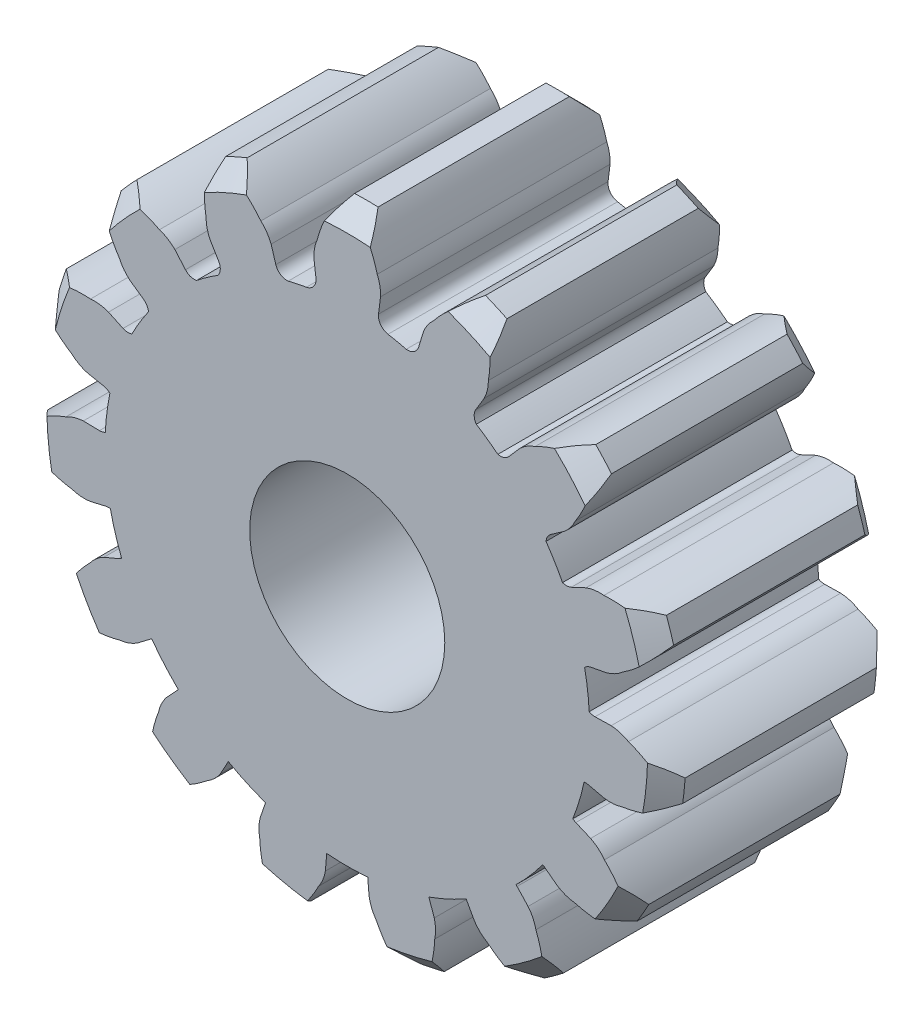
SolidWorks part; units mm, degrees
ref_plane "Front Plane" through (0, 0, 0) normal (0, 0, 1) x (1, 0, 0)
ref_plane "Top Plane" through (0, 0, 0) normal (0, 1, 0) x (1, 0, 0)
ref_plane "Right Plane" through (0, 0, 0) normal (1, 0, 0) x (0, 0, -1)
sketch "Sketch1" plane through (0, 0, 0) normal (0, 0, 1) x (1, 0, 0)
  circle A0 centre (0, 0) radius 6.333
  dimension "Di" = 12.666
extrude "Boss-Extrude1" add sketch "Sketch1" along normal blind 6
sketch "Sketch2" plane through (0, 0, 6) normal (0, 0, 1) x (1, 0, 0)
  line L0 (0, 0) -> (0, 64.154) construction
  line L2 (0.8182, 6.5755) -> (0.8702, 6.9938)
  line L3 (-0.8182, 6.5755) -> (-0.8702, 6.9938)
  line L4 (0.8182, 6.5755) -> (0, 0) construction
  arc A1 (0.0333, 6.7153) -> (0.0333, 6.7153) centre (0, 7.5) cw construction
  arc A8 (-0.3068, 8.4945) -> (0.3068, 8.4945) centre (0, 0) cw
  circle A9 centre (0, 0) radius 6.333
  arc A11 (1.0654, 6.2427) -> (-1.0654, 6.2427) centre (0, 0) ccw
  arc A17 (0.7031, 6.4421) -> (0.7182, 6.441) centre (0.7843, 7.4589) ccw construction
  arc A18 (0.7843, 7.4589) -> (0.8702, 6.9938) centre (-0.1484, 7.0461) cw
  arc A19 (-1.8751, 5.6612) -> (-1.8776, 5.6649) centre (0.7843, 7.4589) ccw construction
  arc A21 (-1.8488, 7.2686) -> (2.7896, 6.9619) centre (0, 0) cw construction
  arc A22 (-5.3112, 4.6326) -> (4.4547, 5.4613) centre (0, 0) cw construction
  arc A23 (0.7843, 7.4589) -> (0.3068, 8.4945) centre (-2.3231, 6.6538) ccw
  arc A24 (1.0654, 6.2427) -> (0.8182, 6.5755) centre (1.1159, 6.5385) cw
  arc A25 (-1.0654, 6.2427) -> (-0.8182, 6.5755) centre (-1.1159, 6.5385) ccw
  arc A26 (-0.7843, 7.4589) -> (-0.8702, 6.9938) centre (0.1484, 7.0461) ccw
  arc A27 (-0.7843, 7.4589) -> (-0.3068, 8.4945) centre (2.3231, 6.6538) cw
  dimension "CT" = 7.0477
  dimension "Dp" = 7.5
  dimension "De" = 8.5
  dimension "e" = 0.7854
  dimension "R1" = 1.02
  dimension "R2" = 3.21
  dimension "D2" = 0.3
  dimension "D1" = 0
sketch "Sketch3" plane through (0, 0, 6) normal (0, 0, 1) x (1, 0, 0)
  line L0 (0, 0) -> (335.0525, 5.0373) construction
  point P3 (174.1457, 3.6183)
  point P4 (212.24, 23.1932)
  point P5 (254.6653, 18.8305)
  dimension "M" = 1
  dimension "angulo de presion" = 20
  dimension "Z" = 15
extrude "Boss-Extrude2" add sketch "Sketch2" against normal through all
chamfer "Chamfer1" distance 0.5 angle 45 2 edges at (0, 8.5, 0) (0, 8.5, 6)
pattern_circular "CirPattern2" count 15 over 360 about axis through (0, 0.1487, 0) along (0, 0, 1) of "Boss-Extrude2", "Chamfer1"
sketch "Sketch4" plane through (0, 0, 6) normal (0, 0, 1) x (1, 0, 0)
  circle A0 centre (0, 0) radius 2.55
  dimension "D1" = 5.1
extrude "Cut-Extrude2" cut sketch "Sketch4" against normal through all
sketch "Sketch5" plane through (0, 0, 0) normal (0, 0, 1) x (1, 0, 0)
  line L1 (0, 5.4848) -> (-4.75, 2.7424)
  line L2 (-4.75, 2.7424) -> (-4.75, -2.7424)
  line L3 (-4.75, -2.7424) -> (0, -5.4848)
  line L4 (0, -5.4848) -> (4.75, -2.7424)
  line L5 (4.75, -2.7424) -> (4.75, 2.7424)
  line L6 (4.75, 2.7424) -> (0, 5.4848)
  circle A1 centre (0, 0) radius 2.55 construction
  circle A2 centre (0, 0) radius 2.55
  circle A3 centre (0, 0) radius 4.75 construction
  dimension "D1" = 9.5
extrude "Cut-Extrude3" cut sketch "Sketch5" along normal blind 2
equation "\"Di@Sketch1\" = 2 * \"Dp@Sketch2\" -  ( 2 * \"M@Sketch3\" * 1.167 ) "
equation "\"D1@Boss-Extrude1\" =  ( 2.15 * pi * \"M@Sketch3\" )  + 5"
equation "\"De@Sketch2\" = \"M@Sketch3\" *  ( \"Z@Sketch3\" + 2 )  / 2"
equation "\"Dp@Sketch2\" = \"M@Sketch3\" * \"Z@Sketch3\" / 2"
equation "\"CT@Sketch2\"=cos ( \"angulo de presion@Sketch3\" )  * \"Dp@Sketch2\""
equation "\"e@Sketch2\"=0.5*\"M@Sketch3\"*pi/2"
equation "\"R1@Sketch2\"=0.068*\"Dp@Sketch2\"*2"
equation "\"R2@Sketch2\"=0.2140*\"Dp@Sketch2\"*2"
equation "\"D2@Sketch2\"=0.3*\"M@Sketch3\""
equation "\"D1@CirPattern2\"=\"Z@Sketch3\""
